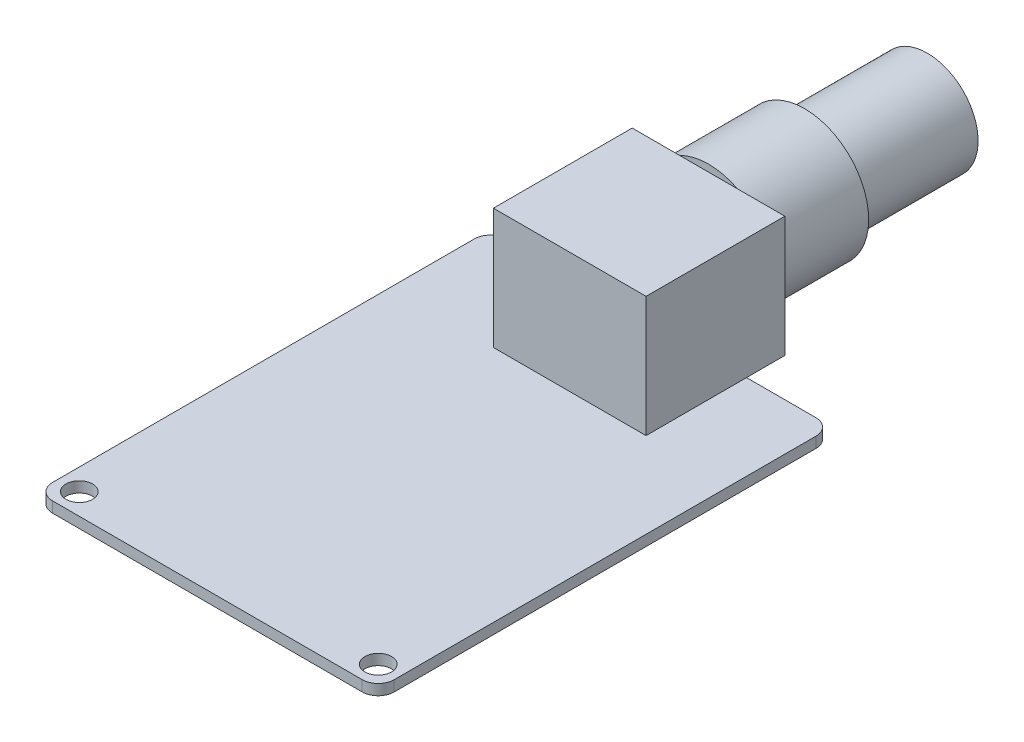
SolidWorks part; units mm, degrees
ref_plane "前基準面" through (0, 0, 0) normal (0, 0, 1) x (1, 0, 0)
ref_plane "上基準面" through (0, 0, 0) normal (0, 1, 0) x (1, 0, 0)
ref_plane "右基準面" through (0, 0, 0) normal (1, 0, 0) x (0, 0, -1)
sketch "草圖1" plane through (0, 0, 0) normal (0, 0, 1) x (1, 0, 0)
  circle A0 centre (-64.3409, 31.5) radius 6
  circle A1 centre (-64.3409, 31.5) radius 6.25 construction
  circle A2 centre (-29.3409, 31.5) radius 6.25 construction
  dimension "D1" = 12
  dimension "D2" = 0
  dimension "D3" = 35
extrude "填料-伸長1" add sketch "草圖1" against normal blind 5.5 and the other way blind 3.5 contours A0
sketch "草圖2" plane through (0, 0, 3.5) normal (0, 0, 1) x (1, 0, 0)
  line L1 (-71.4909, 36.85) -> (-57.1909, 36.85)
  line L2 (-71.4909, 36.85) -> (-71.4909, 25.55)
  line L3 (-71.4909, 25.55) -> (-57.1909, 25.55)
  line L4 (-57.1909, 36.85) -> (-57.1909, 25.55)
  circle A0 centre (-64.3409, 31.5) radius 6 construction
  dimension "D5" = 5.95
  dimension "D1" = 7.15
  dimension "D3" = 11.3
  dimension "D4" = 14.3
extrude "填料-伸長2" add sketch "草圖2" along normal blind 13
sketch "草圖3" plane through (0, 25.55, 0) normal (0, -1, 0) x (1, 0, 0)
  line L0 (-57.1909, 16.5) -> (-57.1909, 3.5) construction
  line L1 (-50.6909, 7.0879) -> (-79.6909, 7.0879)
  line L2 (-49.1909, 8.5879) -> (-49.1909, 48.0879)
  line L3 (-50.6909, 49.5879) -> (-79.6909, 49.5879)
  line L4 (-81.1909, 8.5879) -> (-81.1909, 48.0879)
  circle A0 centre (-51.1909, 47.5879) radius 1.25
  circle A1 centre (-79.1909, 47.5879) radius 1.25
  arc A2 (-79.6909, 7.0879) -> (-81.1909, 8.5879) centre (-79.6909, 8.5879) cw
  arc A3 (-50.6909, 7.0879) -> (-49.1909, 8.5879) centre (-50.6909, 8.5879) ccw
  arc A4 (-79.6909, 49.5879) -> (-81.1909, 48.0879) centre (-79.6909, 48.0879) ccw
  arc A5 (-49.1909, 48.0879) -> (-50.6909, 49.5879) centre (-50.6909, 48.0879) ccw
  point P14 (-81.1909, 7.0879)
  point P19 (-81.1909, 49.5879)
  point P22 (-49.1909, 49.5879)
  dimension "D4" = 2.5
  dimension "D5" = 2.5
  dimension "D6" = 2
  dimension "D10" = 1.5
  dimension "D1" = 32
  dimension "D2" = 42.5
  dimension "D3" = 8
  dimension "D7" = 2
  dimension "D8" = 2
  dimension "D9" = 2
extrude "填料-伸長3" add sketch "草圖3" along normal blind 1
sketch "草圖4" plane through (0, 0, -5.5) normal (0, 0, -1) x (-1, 0, 0)
  circle A0 centre (64.3409, 31.5) radius 4.75
  circle A1 centre (64.3409, 31.5) radius 6 construction
  dimension "D1" = 9.5
  dimension "D2" = 0
extrude "填料-伸長4" add sketch "草圖4" along normal blind 11.5
sketch "草圖5" plane through (0, 0, -17) normal (0, 0, -1) x (-1, 0, 0)
  circle A3 centre (64.3409, 31.5) radius 4.25
  circle A4 centre (64.3409, 31.5) radius 4.25
  dimension "D1" = 0.5
extrude "除料-伸長1" cut sketch "草圖5" against normal blind 11.5
